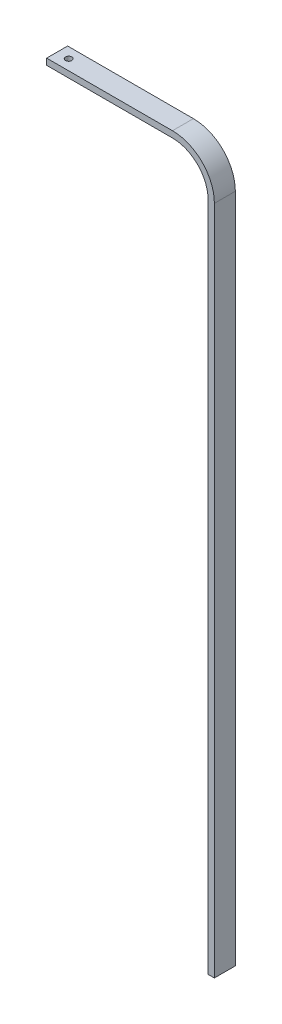
SolidWorks part; units mm, degrees
ref_plane "Front Plane" through (0, 0, 0) normal (0, 0, 1) x (1, 0, 0)
ref_plane "Top Plane" through (0, 0, 0) normal (0, 1, 0) x (1, 0, 0)
ref_plane "Right Plane" through (0, 0, 0) normal (1, 0, 0) x (0, 0, -1)
sketch "Sketch1" plane through (0, 0, 0) normal (0, 0, 1) x (1, 0, 0)
  line L1 (20, 0) -> (17, 0) construction
  line L2 (20, 0) -> (20, -320)
  line L3 (20, -320) -> (17, -320)
  line L4 (17, 0) -> (17, -320)
  line L5 (-60, 20) -> (0, 20)
  line L6 (-60, 20) -> (-60, 17)
  line L7 (-60, 17) -> (0, 17)
  line L8 (0, 20) -> (0, 17) construction
  arc A0 (20, 0) -> (0, 20) centre (0, 0) ccw
  arc A1 (17, 0) -> (0, 17) centre (0, 0) ccw
  arc A2 (-10.5357, 17) -> (17, -10.5357) centre (0, 0) ccw construction
  arc A3 (0, 17) -> (17, 0) centre (0, 0) ccw construction
  arc A4 (0, 20) -> (-10.5357, 17) centre (0, 0) ccw construction
  arc A5 (17, -10.5357) -> (20, 0) centre (0, 0) ccw construction
  dimension "D4" = 40
  dimension "D5" = 34
  dimension "D1" = 3
  dimension "D2" = 80
  dimension "D3" = 340
extrude "Boss-Extrude1" add sketch "Sketch1" along normal blind 10
sketch "Sketch2" plane through (0, 20, 0) normal (0, 1, 0) x (1, 0, 0)
  line L0 (-60, -10) -> (-60, 0) construction
  line L1 (0, -10) -> (-60, -10) construction
  circle A0 centre (-54.5, -5) radius 1.5
  dimension "D1" = 3
  dimension "D2" = 5.5
  dimension "D3" = 5
extrude "Cut-Extrude1" cut sketch "Sketch2" against normal blind 5
